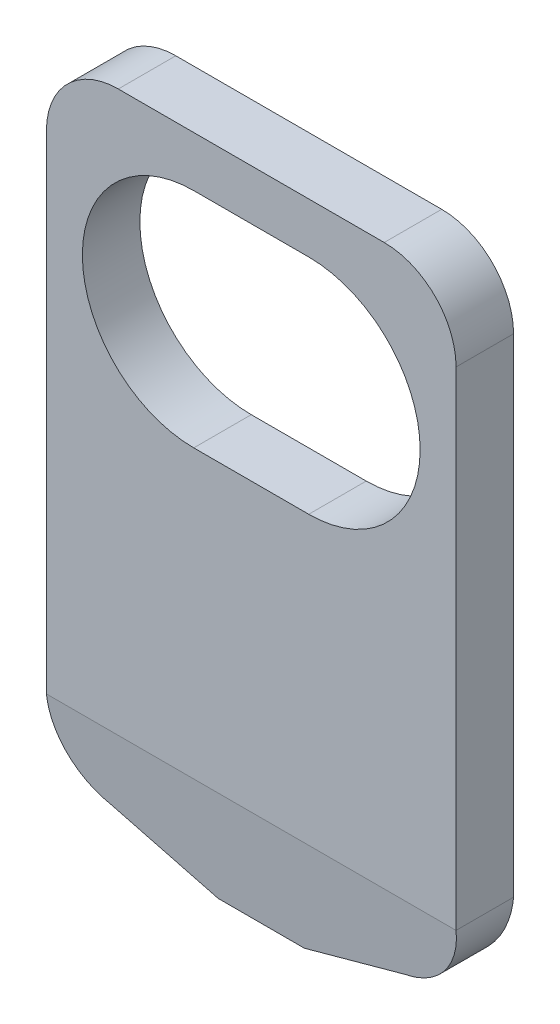
SolidWorks part; units mm, degrees
ref_plane "Front Plane" through (0, 0, 0) normal (0, 0, 1) x (1, 0, 0)
ref_plane "Top Plane" through (0, 0, 0) normal (0, 1, 0) x (1, 0, 0)
ref_plane "Right Plane" through (0, 0, 0) normal (1, 0, 0) x (0, 0, -1)
sketch "Sketch1" plane through (0, 0, 0) normal (0, 0, 1) x (1, 0, 0)
  line L0 (14.25, 46) -> (14.25, 34.75) construction
  line L2 (0, 7.0508) -> (0, 41)
  line L3 (5, 46) -> (23.5, 46)
  line L4 (28.5, 7.0508) -> (28.5, 41)
  line L5 (14.25, 0) -> (14.25, 3) construction
  line L6 (10.25, 34.75) -> (18.25, 34.75) construction
  line L7 (10.25, 42.5) -> (18.25, 42.5)
  line L8 (10.25, 27) -> (18.25, 27)
  line L9 (14.0425, 0.0218) -> (3.9626, 2.1596) construction
  line L10 (14.4575, 0.0218) -> (24.5374, 2.1596) construction
  line L11 (0, 3) -> (28.5, 3) construction
  line L12 (0, 0) -> (0, -5.1694) construction
  line L13 (0, 0) -> (0, 3) construction
  line L14 (14.25, 0) -> (28.5, 0) construction
  line L15 (3.9626, 2.1596) -> (11.25, 0)
  line L16 (14.25, 27) -> (14.25, 0) construction
  line L17 (11.25, 0) -> (17.25, 0)
  line L18 (17.25, 0) -> (24.5374, 2.1596)
  line L19 (14.25, 3) -> (14.25, 0)
  arc A1 (10.25, 42.5) -> (10.25, 27) centre (10.25, 34.75) ccw
  arc A2 (18.25, 42.5) -> (18.25, 27) centre (18.25, 34.75) cw
  arc A3 (28.5, 41) -> (23.5, 46) centre (23.5, 41) ccw
  arc A4 (0, 41) -> (5, 46) centre (5, 41) cw
  arc A5 (14.4575, 0.0218) -> (14.0425, 0.0218) centre (14.25, 1) cw construction
  arc A6 (28.5, 7.0508) -> (24.5374, 2.1596) centre (23.5, 7.0508) cw
  arc A7 (0, 7.0508) -> (3.9626, 2.1596) centre (5, 7.0508) ccw
  point P14 (14.25, 34.75)
  point P28 (28.5, 46)
  point P33 (0, 46)
  point P39 (14.25, 0)
  dimension "D2" = 5
  dimension "D5" = 15.5
  dimension "D6" = 1
  dimension "D9" = 5
  dimension "D1" = 28.5
  dimension "D3" = 27
  dimension "D4" = 8
  dimension "D7" = 3
  dimension "D8" = 46
  dimension "D10" = 6
extrude "Boss-Extrude1" add sketch "Sketch1" along normal blind 4 contours L15 L17 L18 A6 L4 A3 L3 A4 L2 A7 | A2 L8 A1 L7
sketch "Sketch2" plane through (0, 0, 0) normal (-1, 0, 0) x (0, 0, 1)
  line L0 (0, 0) -> (0, 7.0508)
  line L1 (0, 7.0508) -> (0.7, 0)
  line L3 (0.7, 0) -> (0, 0)
  line L4 (2, 0) -> (2, 7.0508) construction
  line L6 (4, 7.0508) -> (0, 7.0508) construction
  line L7 (4, 7.0508) -> (3.3, 0)
  line L8 (4, 0) -> (4, 7.0508)
  line L9 (3.3, 0) -> (4, 0)
  line L10 (4, 0) -> (0, 0) construction
  dimension "D1" = 0.7
extrude "Cut-Extrude1" cut sketch "Sketch2" against normal through all
